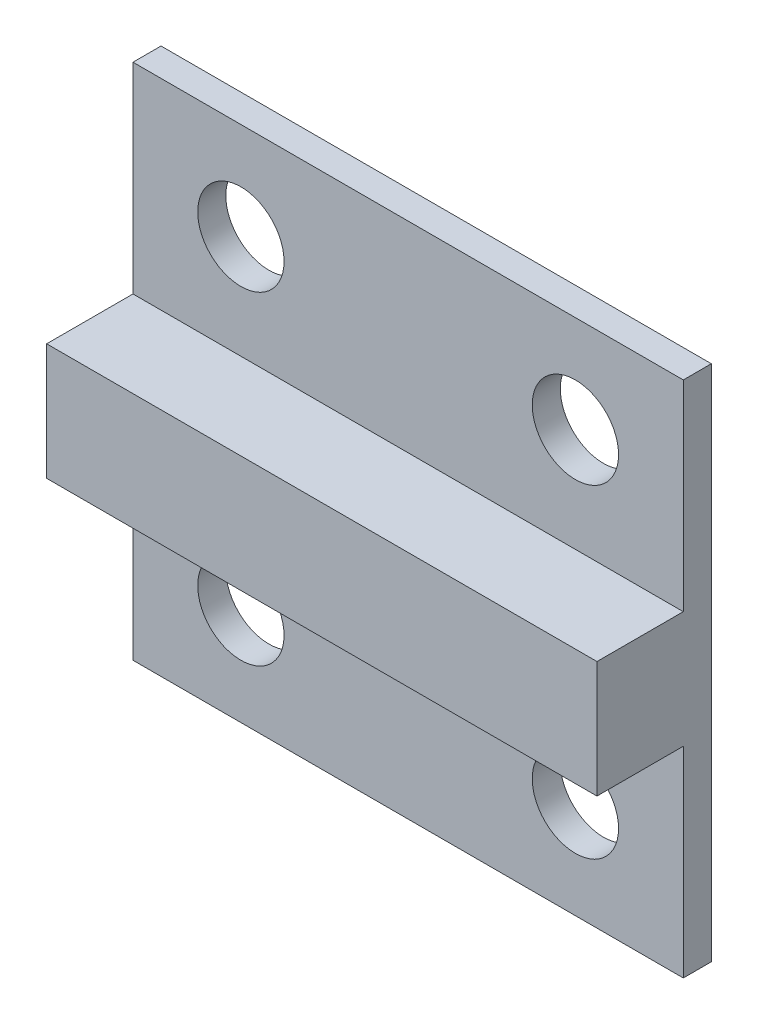
SolidWorks part; units mm, degrees
ref_plane "Front" through (0, 0, 0) normal (0, 0, 1) x (1, 0, 0)
ref_plane "Top" through (0, 0, 0) normal (0, 1, 0) x (1, 0, 0)
ref_plane "Right" through (0, 0, 0) normal (1, 0, 0) x (0, 0, -1)
sketch "Sketch1" plane through (0, 0, 0) normal (0, 0, 1) x (1, 0, 0)
  line L1 (1.8271, 20.9922) -> (27.3271, 20.9922)
  line L2 (1.8271, 20.9922) -> (1.8271, -3.0078)
  line L3 (1.8271, -3.0078) -> (27.3271, -3.0078)
  line L4 (27.3271, 20.9922) -> (27.3271, -3.0078)
  dimension "D1" = 24
  dimension "D2" = 25.5
extrude "Boss-Extrude1" add sketch "Sketch1" along normal blind 1.3
sketch "Sketch2" plane through (0, 0, 1.3) normal (0, 0, 1) x (1, 0, 0)
  line L2 (1.8271, 20.9922) -> (1.8271, -3.0078) construction
  line L3 (1.8271, 11.6922) -> (27.3271, 11.6922)
  line L4 (1.8271, 11.6922) -> (1.8271, 6.2922)
  line L5 (1.8271, 6.2922) -> (27.3271, 6.2922)
  line L6 (27.3271, 11.6922) -> (27.3271, 6.2922)
  line L7 (27.3271, -3.0078) -> (27.3271, 20.9922) construction
  line L8 (27.3271, 20.9922) -> (1.8271, 20.9922) construction
  line L9 (1.8271, -3.0078) -> (27.3271, -3.0078) construction
  dimension "D2" = 9.3
  dimension "D3" = 9.3
extrude "Boss-Extrude2" add sketch "Sketch2" along normal blind 4
sketch "Sketch3" plane through (0, 0, 1.3) normal (0, 0, 1) x (1, 0, 0)
  line L5 (1.8271, 20.9922) -> (1.8271, 11.6922) construction
  line L7 (27.3271, 20.9922) -> (1.8271, 20.9922) construction
  line L9 (27.3271, 11.6922) -> (27.3271, 20.9922) construction
  circle A0 centre (22.3271, 16.4922) radius 2
  circle A1 centre (6.8271, 16.4922) radius 2
  point P4 (0, 0)
  dimension "D1" = 4
  dimension "D2" = 3
  dimension "D3" = 2.5
  dimension "D4" = 2.5
  dimension "D5" = 3
extrude "Cut-Extrude1" cut sketch "Sketch3" against normal blind 4
sketch "Sketch4" plane through (0, 0, 1.3) normal (0, 0, 1) x (1, 0, 0)
  line L2 (1.8271, 6.2922) -> (1.8271, -3.0078) construction
  line L4 (1.8271, -3.0078) -> (27.3271, -3.0078) construction
  line L6 (27.3271, -3.0078) -> (27.3271, 6.2922) construction
  circle A0 centre (6.8271, 1.4922) radius 2
  circle A1 centre (22.3271, 1.4922) radius 2
  dimension "D1" = 4
  dimension "D2" = 3
  dimension "D3" = 2.5
  dimension "D4" = 3
  dimension "D5" = 4.5
extrude "Cut-Extrude2" cut sketch "Sketch4" against normal blind 4
